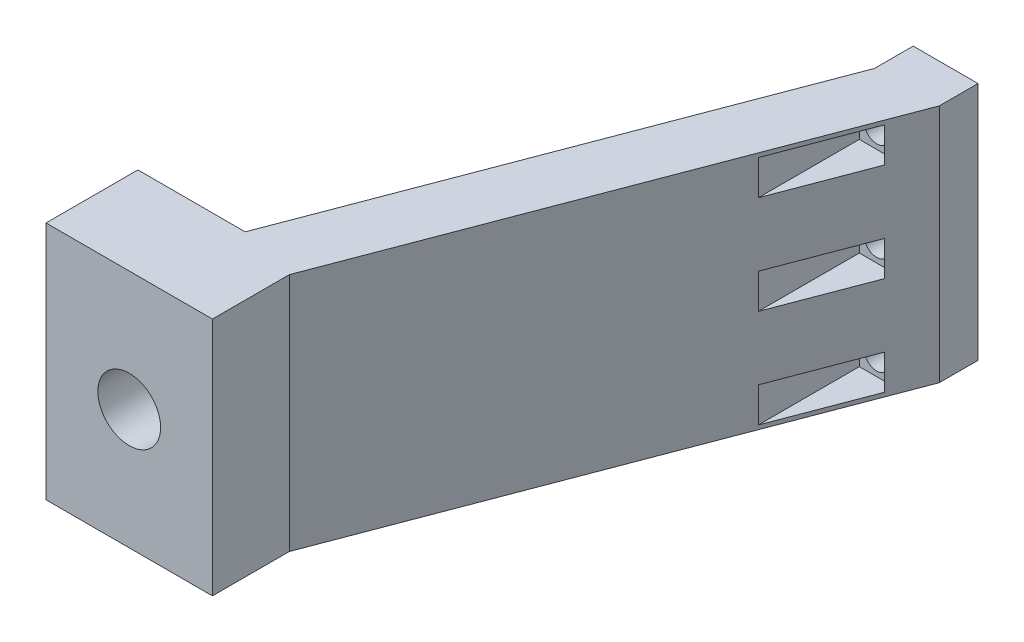
SolidWorks part; units mm, degrees
ref_plane "Front Plane" through (0, 0, 0) normal (0, 0, 1) x (1, 0, 0)
ref_plane "Top Plane" through (0, 0, 0) normal (0, 1, 0) x (1, 0, 0)
ref_plane "Right Plane" through (0, 0, 0) normal (1, 0, 0) x (0, 0, -1)
sketch "Sketch4" plane through (0, 0, 0) normal (0, 0, 1) x (1, 0, 0)
  line L0 (241.3, -9.8933) -> (241.3, -7.1526) construction
  line L5 (232.9346, -69.0474) -> (249.6654, -69.0474)
  line L6 (232.9346, -69.0474) -> (232.9346, -7.1526)
  line L7 (232.9346, -7.1526) -> (249.6654, -7.1526)
  line L16 (249.6654, -69.0474) -> (249.6654, -7.1526)
  line L17 (241.3, -66.3067) -> (241.3, -69.0474) construction
  line L18 (238.4933, -38.1) -> (232.9346, -38.1) construction
  line L19 (244.1067, -38.1) -> (249.6654, -38.1) construction
  circle A3 centre (241.3, -12.7) radius 3.0482
  circle A4 centre (241.3, -38.1) radius 3.0482
  circle A5 centre (241.3, -63.5) radius 3.0482
  point P0 (0, 0)
extrude "Boss-Extrude4" add sketch "Sketch4" along normal blind 10
sketch "Sketch5" plane through (0, -69.0474, 0) normal (0, -1, 0) x (1, 0, 0)
  line L0 (249.6654, 10) -> (203.5094, 131.6152)
  line L1 (232.9346, 10) -> (188.2485, 127.7424)
  line L2 (179.5552, 151.4629) -> (179.564, 131.4629) construction
  line L4 (203.5094, 131.6152) -> (203.5094, 151.4629)
  line L5 (203.5094, 151.4629) -> (160.5452, 151.4629)
  line L6 (160.5452, 127.7424) -> (160.5452, 151.4629)
  line L7 (160.5452, 127.7424) -> (188.2485, 127.7424)
  line L8 (232.9346, 10) -> (249.6654, 10)
  point P1 (182.7629, 155.0148)
  point P8 (188.2485, 127.7424)
  point P9 (164.6327, 127.7424)
  point P14 (179.564, 131.6152)
  point P15 (0, 0)
  point P16 (179.564, 151.4629)
  dimension "D1" = 20
extrude "Boss-Extrude5" add sketch "Sketch5" against normal up to surface (61.8948 mm away) up to face at (241.3, -7.1526, 5)
sketch "Sketch6" plane through (0, 0, 0) normal (0, 0, -1) x (-1, 0, 0)
  circle A0 centre (-241.3, -63.5) radius 3.2278
  circle A1 centre (-241.3, -38.1) radius 3.2278
  circle A2 centre (-241.3, -12.7) radius 3.2278
extrude "Cut-Extrude1" cut sketch "Sketch6" against normal through all
sketch "Sketch8" plane through (0, 0, 0) normal (0, 0, 1) x (1, 0, 0)
  line L1 (245.7884, -67.9884) -> (236.8116, -67.9884)
  line L2 (245.7884, -67.9884) -> (245.7884, -59.0116)
  line L3 (245.7884, -59.0116) -> (236.8116, -59.0116)
  line L4 (236.8116, -67.9884) -> (236.8116, -59.0116)
  line L5 (245.7884, -67.9884) -> (236.8116, -59.0116) construction
  line L6 (245.7884, -59.0116) -> (236.8116, -67.9884) construction
  line L11 (245.7884, -42.5884) -> (236.8116, -42.5884)
  line L12 (241.3, -69.0474) -> (241.3, -7.1526) construction
  line L13 (249.6654, -69.0474) -> (203.5094, -69.0474) construction
  line L14 (203.5094, -7.1526) -> (249.6654, -7.1526) construction
  line L15 (244.5278, -38.1) -> (227.585, -38.1) construction
  line L16 (244.5278, -12.7) -> (232.5689, -12.7) construction
  line L17 (245.7884, -42.5884) -> (245.7884, -33.6116)
  line L18 (245.7884, -33.6116) -> (236.8116, -33.6116)
  line L19 (236.8116, -42.5884) -> (236.8116, -33.6116)
  line L20 (245.7884, -42.5884) -> (236.8116, -33.6116) construction
  line L21 (245.7884, -33.6116) -> (236.8116, -42.5884) construction
  line L22 (245.7884, -8.2116) -> (236.8116, -8.2116)
  line L23 (245.7884, -8.2116) -> (245.7884, -17.1884)
  line L24 (245.7884, -17.1884) -> (236.8116, -17.1884)
  line L25 (236.8116, -8.2116) -> (236.8116, -17.1884)
  line L26 (245.7884, -8.2116) -> (236.8116, -17.1884) construction
  line L27 (245.7884, -17.1884) -> (236.8116, -8.2116) construction
  circle A1 centre (241.3, -38.1) radius 3.2278 construction
  circle A2 centre (241.3, -12.7) radius 3.2278 construction
  point P0 (241.3, -63.5)
  point P6 (241.3, -38.1)
  point P18 (241.3, -12.7)
  point P31 (0, 0)
  point P32 (245.7884, -33.6116)
extrude "Cut-Extrude2" cut sketch "Sketch8" along normal blind 30.32 from offset 17.78
sketch "Sketch9" plane through (0, 0, 151.4629) normal (0, 0, 1) x (1, 0, 0)
  line L0 (182.0273, -69.0474) -> (182.0273, -7.1526) construction
  line L1 (203.5094, -69.0474) -> (160.5452, -69.0474) construction
  line L2 (160.5452, -7.1526) -> (203.5094, -7.1526) construction
  line L3 (160.5452, -38.1) -> (203.5094, -38.1) construction
  line L4 (160.5452, -7.1526) -> (160.5452, -69.0474) construction
  line L5 (203.5094, -7.1526) -> (203.5094, -69.0474) construction
  circle A0 centre (182.0273, -38.1) radius 3.75
  dimension "D1" = 7.5
extrude "Cut-Extrude3" cut sketch "Sketch9" against normal blind 30.32
sketch "Sketch10" plane through (0, 0, 151.4629) normal (0, 0, 1) x (1, 0, 0)
  circle A0 centre (182.0273, -38.1) radius 8.1
  dimension "D1" = 16.2
extrude "Cut-Extrude4" cut sketch "Sketch10" against normal blind 20
